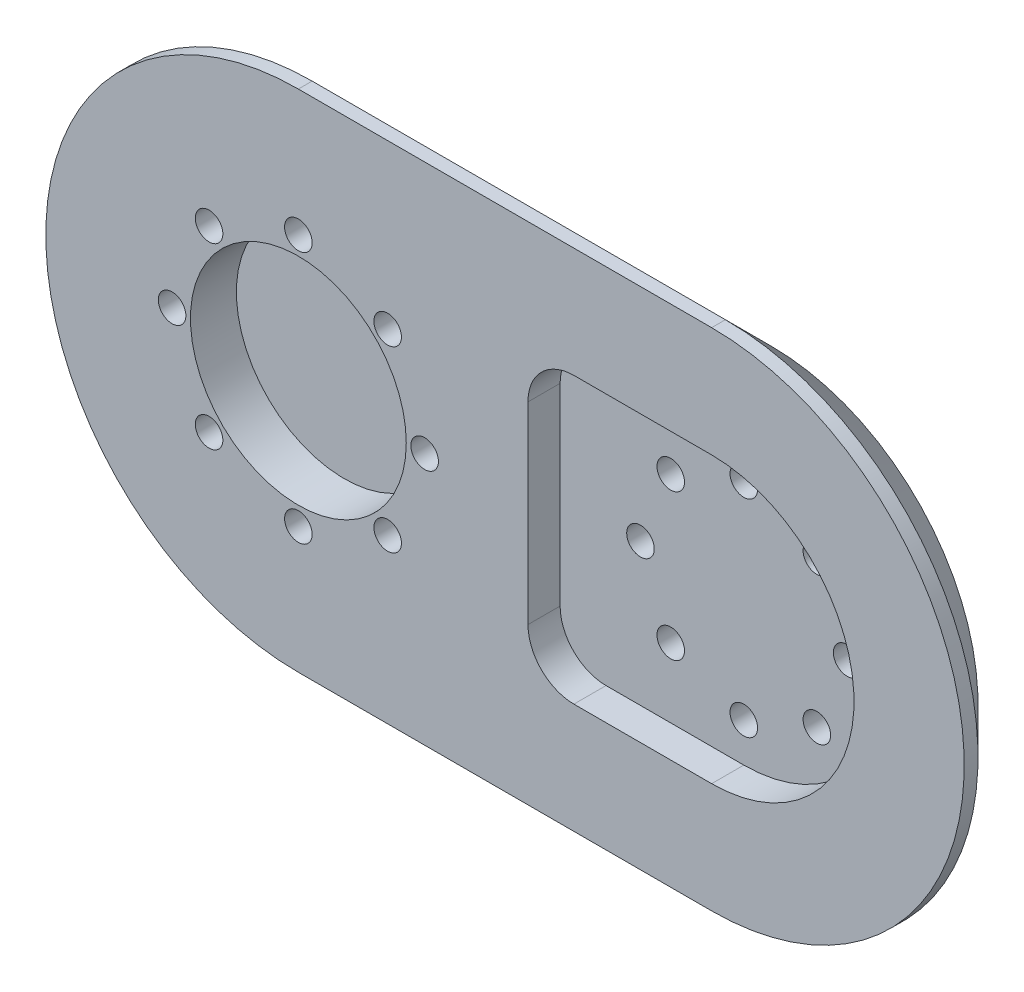
SolidWorks part; units mm, degrees
ref_plane "前视基准面" through (0, 0, 0) normal (0, 0, 1) x (1, 0, 0)
ref_plane "上视基准面" through (0, 0, 0) normal (0, 1, 0) x (1, 0, 0)
ref_plane "右视基准面" through (0, 0, 0) normal (1, 0, 0) x (0, 0, -1)
sketch "草图1" plane through (0, 0, 0) normal (0, 0, 1) x (1, 0, 0)
  line L0 (0, 55) -> (90, 55)
  line L1 (0, -55) -> (90, -55)
  arc A0 (0, 55) -> (0, -55) centre (0, 0) ccw
  arc A1 (90, -55) -> (90, 55) centre (90, 0) ccw
  dimension "D1" = 110
  dimension "D2" = 90
extrude "拉伸1" add sketch "草图1" along normal blind 13
sketch "草图2" plane through (0, 0, 13) normal (0, 0, 1) x (1, 0, 0)
  circle A0 centre (90, 0) radius 31
  dimension "D1" = 62
extrude "切除-拉伸3" cut sketch "草图2" against normal blind 7
sketch "草图4" plane through (0, 0, 0) normal (0, 0, -1) x (-1, 0, 0)
  circle A1 centre (-90, 22.5) radius 3
  circle A2 centre (-74.0901, 15.9099) radius 3
  circle A3 centre (-67.5, 0) radius 3
  circle A4 centre (-74.0901, -15.9099) radius 3
  circle A5 centre (-90, -22.5) radius 3
  circle A6 centre (-105.9099, -15.9099) radius 3
  circle A7 centre (-112.5, 0) radius 3
  circle A8 centre (-105.9099, 15.9099) radius 3
  dimension "D1" = 6
extrude "切除-拉伸4" cut sketch "草图4" against normal blind 31
chamfer "倒角1" distance 10 angle 45 4 edges at (45, -55, 0) (145, 0, 0) (-55, 0, 0) (45, 55, 0)
sketch "草图5" plane through (0, 0, 13) normal (0, 0, 1) x (1, 0, 0)
  line L4 (50, 31) -> (90, 31)
  line L5 (50, 31) -> (50, -31)
  line L6 (50, -31) -> (90, -31)
  arc A1 (90, -31) -> (90, 31) centre (90, 0) ccw
extrude "切除-拉伸5" cut sketch "草图5" against normal blind 7
sketch "草图7" plane through (0, 0, 0) normal (0, 0, -1) x (-1, 0, 0)
  circle A1 centre (19.4454, 19.4454) radius 3
  circle A2 centre (27.5, 0) radius 3
  circle A3 centre (19.4454, -19.4454) radius 3
  circle A4 centre (0, -27.5) radius 3
  circle A5 centre (0, 27.5) radius 3
  circle A6 centre (-19.4454, -19.4454) radius 3
  circle A7 centre (-27.5, 0) radius 3
  circle A8 centre (-19.4454, 19.4454) radius 3
extrude "切除-拉伸7" cut sketch "草图7" against normal blind 80
fillet "圆角1" radius 10 2 edges at (50, -31, 9.5) (50, 31, 9.5)
sketch "草图8" plane through (0, 0, 13) normal (0, 0, 1) x (1, 0, 0)
  circle A0 centre (0, 0) radius 23.5
  dimension "D1" = 47
extrude "切除-拉伸8" cut sketch "草图8" against normal blind 10
